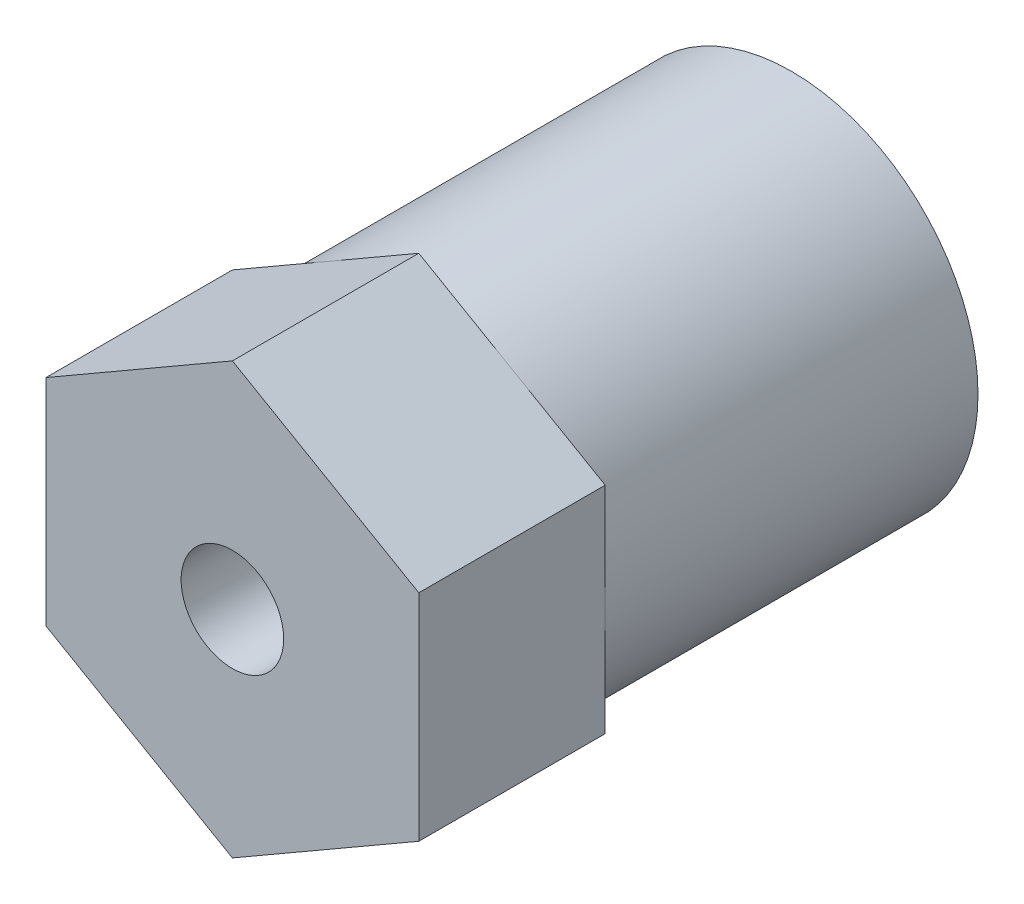
SolidWorks part; units mm, degrees
ref_plane "前视基准面" through (0, 0, 0) normal (0, 0, 1) x (1, 0, 0)
ref_plane "上视基准面" through (0, 0, 0) normal (0, 1, 0) x (1, 0, 0)
ref_plane "右视基准面" through (0, 0, 0) normal (1, 0, 0) x (0, 0, -1)
other "Configuration Table"
sketch "Profile_1" plane through (0, 0, 0) normal (0, 0, 1) x (1, 0, 0)
  circle A0 centre (0, 0) radius 6
  circle A1 centre (0, 0) radius 4
extrude "Shaft_socket" add sketch "Profile_1" along normal blind 12 from offset 12
sketch "Profile_2" plane through (0, 0, 0) normal (0, 0, 1) x (1, 0, 0)
  line L0 (6, 3.4641) -> (0, 6.9282)
  line L1 (0, 6.9282) -> (-6, 3.4641)
  line L2 (-6, 3.4641) -> (-6, -3.4641)
  line L3 (-6, -3.4641) -> (0, -6.9282)
  line L4 (0, -6.9282) -> (6, -3.4641)
  line L5 (6, -3.4641) -> (6, 3.4641)
  circle A0 centre (0, 0) radius 1.65
extrude "Drive_hex" add sketch "Profile_2" along normal blind 6 from offset 0
